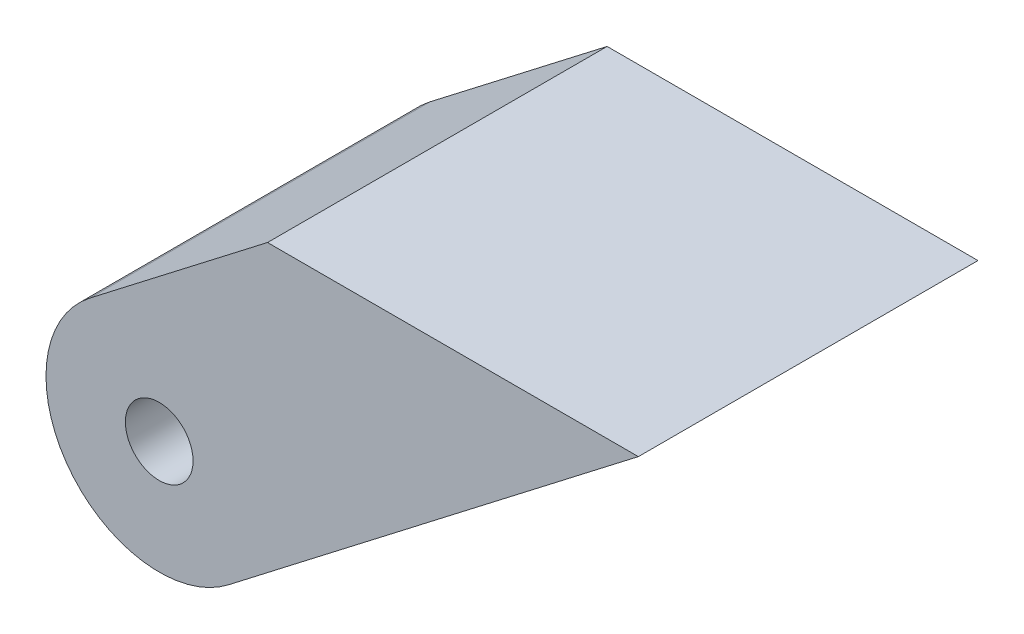
SolidWorks part; units mm, degrees
material "Custom Plastic"
ref_plane "Front Plane" through (0, 0, 0) normal (0, 0, 1) x (1, 0, 0)
ref_plane "Top Plane" through (0, 0, 0) normal (0, 1, 0) x (1, 0, 0)
ref_plane "Right Plane" through (0, 0, 0) normal (1, 0, 0) x (0, 0, -1)
sketch "Sketch1" plane through (0, 0, 0) normal (0, 0, 1) x (1, 0, 0)
  line L0 (0, 0) -> (6.0747, 0) construction
  line L1 (6.0747, 0) -> (6.0747, 12.7) construction
  line L2 (6.0747, 12.7) -> (-3.8767, 5.0293)
  line L3 (3.8767, -5.0293) -> (26.8772, 12.7)
  line L4 (6.0747, 12.7) -> (26.8772, 12.7)
  arc A0 (-3.8767, 5.0293) -> (3.8767, -5.0293) centre (0, 0) ccw
  dimension "D3" = 12.7
  dimension "D1" = 6.0747
  dimension "D2" = 12.7
extrude "Boss-Extrude1" add sketch "Sketch1" along normal blind 19.05
hole_wizard "#6 Clearance Hole1" positions "3DSketch2" profile "Sketch3" hole size "#6" standard "ANSI Inch" end condition through all
sketch3d "3DSketch2"
  point P0 (0, 0, 19.05)
sketch "Sketch3" plane through (0, 0, 19.05) normal (1, 0, 0) x (0, -1, 0)
  line L0 (0, 0) -> (0, 19.05)
  line L1 (0, 19.05) -> (1.8986, 19.05)
  line L2 (1.8986, 19.05) -> (1.8986, 0)
  line L5 (1.8986, 0) -> (0, 0)
  line L11 (0, -6.35) -> (0, 107.95) construction
  dimension "Thru Hole Dia." = 3.7973
  dimension "Thru Hole Depth" = 19.05
